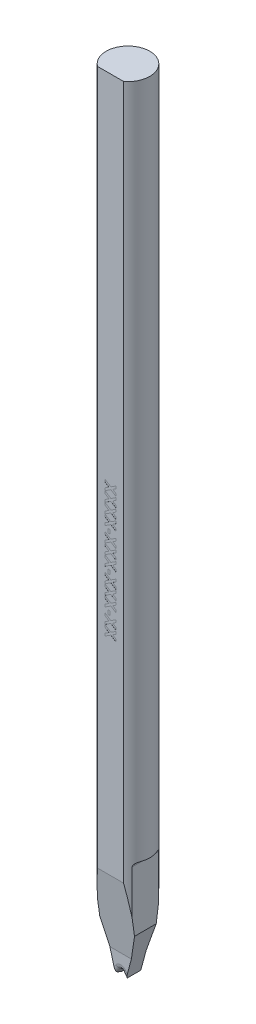
SolidWorks part; units mm, degrees
ref_plane "Ebene vorne" through (0, 0, 0) normal (0, 0, 1) x (1, 0, 0)
ref_plane "Ebene oben" through (0, 0, 0) normal (0, 1, 0) x (1, 0, 0)
ref_plane "Ebene rechts" through (0, 0, 0) normal (1, 0, 0) x (0, 0, -1)
sketch "sketch_TL_cutting" plane through (0, 0, 0) normal (0, 1, 0) x (1, 0, 0)
  circle A0 centre (0, 0) radius 1.9977
extrude "TL_cutting" add sketch "sketch_TL_cutting" along normal blind 72.009
sketch "sketch_TDF_grinding" plane through (0, 0, 0) normal (0, 1, 0) x (1, 0, 0)
  line L0 (0, 0) -> (0, -1.6015) construction
  line L1 (-2.0077, -5.6169) -> (2.0077, -5.6169)
  line L2 (-2.0077, -5.6169) -> (-2.0077, -1.6015)
  line L3 (-2.0077, -1.6015) -> (2.0077, -1.6015)
  line L4 (2.0077, -5.6169) -> (2.0077, -1.6015)
  circle A1 centre (0, 0) radius 1.9977 construction
  point P9 (0, -5.6169)
  dimension "TD_2Offset_X" = 4.0154
  dimension "TD_2Offset_Z" = 4.0154
extrude "TDF_grinding" cut sketch "sketch_TDF_grinding" along normal through all
sketch "sketch_engraving" plane through (0, 0, 1.6015) normal (0, 0, 1) x (1, 0, 0)
  line L0 (1.1942, 72.009) -> (-1.1942, 72.009) construction
  line L6 (-1.1942, 0) -> (1.1942, 0) construction
  line L7 (0, 0) -> (0, 39.605) construction
  line L8 (-0.5, 39.605) -> (-0.5, 0) construction
  text T0 "XXXX-XXX-XXX-XX" font "Arial" height 1
  dimension "D2" = 0.5
  dimension "EngravingStart" = 32.404
extrude "engraving" cut sketch "sketch_engraving" against normal blind 0.005
sketch "sketch_VW_VR_grinding" plane through (0, 0, 0) normal (0, 0, 1) x (1, 0, 0)
  line L0 (-1.59, -0.01) -> (-1.59, 9.682)
  line L1 (1.59, -0.01) -> (1.59, 9.682)
  line L2 (-1.59, 0) -> (1.59, 0) construction
  line L3 (-2.0077, 10) -> (-1.908, 10)
  line L4 (1.908, 10) -> (2.0077, 10)
  line L5 (-2.0077, 10) -> (-2.0077, -0.01)
  line L6 (-2.0077, -0.01) -> (-1.59, -0.01)
  line L7 (1.59, -0.01) -> (2.0077, -0.01)
  line L8 (2.0077, -0.01) -> (2.0077, 10)
  line L9 (-1.908, 10) -> (-1.908, 9.682) construction
  line L10 (-1.59, 9.682) -> (-1.908, 9.682) construction
  line L11 (1.59, 9.682) -> (1.908, 9.682) construction
  line L12 (1.908, 10) -> (1.908, 9.682) construction
  arc A0 (-1.908, 10) -> (-1.59, 9.682) centre (-1.908, 9.682) cw
  arc A2 (1.59, 9.682) -> (1.908, 10) centre (1.908, 9.682) cw
  dimension "D1" = 0.01
  dimension "D4" = 4.0154
extrude "VW_VR_grinding" cut sketch "sketch_VW_VR_grinding" against normal blind 2.0077 and the other way blind 2.0077
sketch "sketch_ISA_grinding" plane through (0, 0, 0) normal (0, 0, 1) x (1, 0, 0)
  line L0 (-0.5004, 0) -> (-2.0077, 5.6254)
  line L4 (2.0077, 5.6254) -> (0.5004, 0)
  line L5 (0.5004, 0) -> (-0.5004, 0)
  line L6 (0, 0) -> (0, 30.49) construction
  line L7 (-2.0077, 5.6254) -> (-2.0077, -0.01)
  line L12 (-2.0077, -0.01) -> (2.0077, -0.01)
  line L13 (2.0077, -0.01) -> (2.0077, 5.6254)
  dimension "ISA" = 30
  dimension "TD_2Offset" = 4.0154
  dimension "Offset" = 0.01
extrude "ISA_grinding" cut sketch "sketch_ISA_grinding" against normal blind 2.0077 and the other way blind 2.0077
sketch "sketch_pre_FRX_BRX" plane through (0, 0, 0) normal (1, 0, 0) x (0, 0, -1)
  line L0 (1.9977, -0.01) -> (1.9977, 3.9152) construction
  line L1 (-1.6015, -0.01) -> (-1.6015, 1.7909) construction
  line L2 (-0.6744, -0.01) -> (-0.6744, 1.7909)
  line L3 (-0.6744, 1.7909) -> (-2.0077, 1.7909)
  line L4 (-2.0077, 1.7909) -> (-2.0077, -0.01)
  line L5 (-2.0077, -0.01) -> (-0.6744, -0.01)
  line L6 (0.6744, -0.01) -> (0.6744, 1.7909)
  line L7 (0.6744, 1.7909) -> (2.0077, 1.7909)
  line L8 (2.0077, 1.7909) -> (2.0077, -0.01)
  line L9 (2.0077, -0.01) -> (0.6744, -0.01)
  dimension "D3" = 0.01
  dimension "D4" = 1.8009
  dimension "D5" = 4.0154
  dimension "D6" = 1.3487
  dimension "D2" = 0.01
  dimension "D7" = 2.6721
extrude "pre_FRX_BRX" cut sketch "sketch_pre_FRX_BRX" against normal blind 2.0077 and the other way blind 2.0077
sketch "sketch_contour_V-Groove" plane through (0, 0, 0) normal (1, 0, 0) x (0, 0, -1)
  line L0 (-1.6015, 0.3556) -> (0, 0.3556)
  line L1 (0, 0.3556) -> (1.9977, 0.3556)
  line L2 (1.9977, -0.8411) -> (1.9977, 1.3178) construction
  line L3 (-1.6015, -0.9209) -> (-1.6015, 1.9363) construction
  line L4 (-1.6015, 0) -> (1.9977, 0) construction
  line L5 (0.6744, 0) -> (0.6744, 0.3556) construction
  line L6 (-0.6744, 0) -> (-0.6744, 0.3556) construction
  dimension "D1" = 0
ref_plane "front" through (0, 0, 1.6015) normal (0, 0, 1) x (1, 0, 0)
ref_plane "back" through (0, 0, -1.9977) normal (0, 0, 1) x (1, 0, 0)
sketch "sketch_section_V-Groove" plane through (0, 0, 1.6015) normal (0, 0, 1) x (1, 0, 0)
  line L0 (-2.7655, -3.556) -> (-0.0419, 0.3338)
  line L2 (0.0419, 0.3338) -> (2.7655, -3.556)
  line L3 (-2.7655, -3.556) -> (2.7655, -3.556)
  line L4 (0, -3.556) -> (0, 0.3556) construction
  line L5 (-0.2756, 0) -> (0.2756, 0) construction
  arc A0 (0.0419, 0.3338) -> (-0.0419, 0.3338) centre (0, 0.3045) ccw
  dimension "GA" = 70
sweep "V-Groove_EDM" cut profiles "sketch_section_V-Groove" path "sketch_contour_V-Groove"
fillet "FR_EDM" radius 0.5004 3 edges at (0.1587, 0.1669, 0.6744) (0, 0.3556, 0.6744) (-0.1587, 0.1669, 0.6744)
fillet "BR_EDM" radius 0.2489 3 edges at (0.1587, 0.1669, -0.6744) (0, 0.3556, -0.6744) (-0.1587, 0.1669, -0.6744)
sketch "sketch_FA_BA_grinding" plane through (0, 0, 0) normal (1, 0, 0) x (0, 0, -1)
  line L2 (2.9977, 18.3323) -> (2.9977, -0.1)
  line L3 (2.9977, -0.1) -> (0.6744, -0.1)
  line L5 (0.6744, -0.1) -> (0.6744, 1.8009)
  line L6 (0.6744, 1.8009) -> (2.9977, 18.3323)
  line L7 (1.9977, -0.1) -> (1.9977, 11.2169) construction
  line L8 (-1.6015, 8.3975) -> (-1.6015, -0.1) construction
  line L9 (-3.6221, 22.7749) -> (-0.6744, 1.8009)
  line L10 (-0.6744, 1.8009) -> (-0.6744, -0.1)
  line L11 (-0.6744, -0.1) -> (-3.6221, -0.1)
  line L12 (-3.6221, -0.1) -> (-3.6221, 22.7749)
  line L13 (-0.6744, 1.8009) -> (0.6744, 1.8009) construction
  dimension "D4" = 1
  dimension "D1" = 0.1
  dimension "FA" = 8
  dimension "BA" = 8
extrude "FA_BA_grinding" cut sketch "sketch_FA_BA_grinding" against normal blind 2.0077 and the other way blind 2.0077
sketch "sketch_groove_dimensions" plane through (0, 0, 0) normal (1, 0, 0) x (0, 0, -1)
  line L0 (-0.174, 0.3556) -> (0.4255, 0.3556)
  line L1 (-0.6744, 0) -> (-0.6744, 0.856) construction
  line L2 (1.9977, 0) -> (1.9977, 0.4166) construction
  line L3 (0.6744, 0) -> (0.6744, 0.6045) construction
  line L4 (-1.6015, 0) -> (-1.6015, 0.3999) construction
  arc A0 (0.4255, 0.3556) -> (0.6744, 0.6045) centre (0.4255, 0.6045) ccw
  arc A1 (-0.174, 0.3556) -> (-0.6744, 0.856) centre (-0.174, 0.856) cw
equation "\"_Offset\"=0.01mm"
equation "\"TL\"=72.009mm"
equation "\"TD\"=3.99542mm"
equation "\"TDF\"=3.59918mm"
equation "\"BA\"=8deg"
equation "\"ISA\"=30deg"
equation "\"FA\"=8deg"
equation "\"GR\"=0.0508mm"
equation "\"GA\"=70deg"
equation "\"GD\"=0.3556mm"
equation "\"FL\"=1.34874mm"
equation "\"F\"=0.59944mm"
equation "\"FX\"=0mm"
equation "\"B\"=0.55118mm"
equation "\"VW\"=3.18008mm"
equation "\"cleaned_VR\"= IIF ( \"VR\" > 0 , \"VR\" , \"E\" - \"_Offset\" )"
equation "\"cleaned_VW\"= IIF ( \"VW\" > 0 , \"VW\" , \"TD\" - \"_Offset\" )"
equation "\"back_edge\"= \"TD\" / 2 - \"X\""
equation "\"side_edge_Offset\"= \"TD\" / 2 + \"_Offset\""
equation "\"TD@sketch_TL_cutting\"=\"TD\""
equation "\"TL@TL_cutting\"=\"TL\""
equation "\"TDF@sketch_TDF_grinding\"=\"TDF\""
equation "\"TD_2Offset_X@sketch_TDF_grinding\"=\"TD\"+2*\"_Offset\""
equation "\"TD_2Offset_Z@sketch_TDF_grinding\"=\"TD\"+2*\"_Offset\""
equation "\"TL_Offset\"= \"TL\" + \"_Offset\""
equation "\"ISA@sketch_ISA_grinding\"=\"ISA\""
equation "\"W@sketch_ISA_grinding\"=\"W\""
equation "\"TD_2Offset@sketch_ISA_grinding\"=\"TD\"+2*\"_Offset\""
equation "\"Offset@sketch_ISA_grinding\"=\"_Offset\""
equation "\"05TD_Offset_posZ@ISA_grinding\"=\"side_edge_Offset\""
equation "\"05TD_Offset_negZ@ISA_grinding\"=\"side_edge_Offset\""
equation "\"E\"=1.80086mm"
equation "\"cleaned_X\"= IIF ( \"X\" > 0 , \"X\" , \"TD\" / 2 - \"FL\" / 2 )"
equation "\"FR\"=0.50038mm"
equation "\"BR\"=0.24892mm"
equation "\"D1\"= \"side_edge_Offset\""
equation "\"D2\"= \"side_edge_Offset\""
equation "\"TDF@sketch_FA_BA_grinding\" = \"TDF\""
equation "\"FL@sketch_FA_BA_grinding\"=\"FL\""
equation "\"E@sketch_FA_BA_grinding\" = \"E\""
equation "\"D1@FA_BA_grinding\"=\"side_edge_Offset\""
equation "\"D2@FA_BA_grinding\"=\"side_angle_Offset\""
equation "\"10GD@sketch_section_V-Groove\" = 10 * \"GD\""
equation "\"GA@sketch_section_V-Groove\" = \"GA\""
equation "\"GD@sketch_section_V-Groove\" = \"GD\""
equation "\"B@sketch_section_V-Groove\" = \"B\""
equation "\"GD@sketch_contour_V-Groove\" = \"GD\""
equation "\"cleaned_FRX\"= IIF ( \"FRX\" > 0 , \"FRX\" , \"FR\" )"
equation "\"cleaned_BRX\"= IIF ( \"BRX\" > 0 , \"BRX\" , \"BR\" )"
equation "\"FL_groove_angle\"=0deg"
equation "\"D3@sketch_pre_FRX_BRX\" = \"_Offset\""
equation "\"D4@sketch_pre_FRX_BRX\" = \"E\""
equation "\"D5@sketch_pre_FRX_BRX\" = 2 * \"side_edge_Offset\""
equation "\"D6@sketch_pre_FRX_BRX\" = \"FL\" + ( \"FR\" - \"cleaned_FRX\" ) + ( \"BR\" - \"cleaned_BRX\" )"
equation "\"TD/2@sketch_pre_FRX_BRX\" = \"TD\" / 2"
equation "\"TDF@sketch_pre_FRX_BRX\" = \"TDF\""
equation "\"D2@sketch_pre_FRX_BRX\" = \"_Offset\""
equation "\"D1@pre_FRX_BRX\" = \"side_edge_Offset\""
equation "\"D2@pre_FRX_BRX\" = \"side_edge_Offset\""
equation "\"D1@BR_EDM\"=\"BR\""
equation "\"TD/2@sketch_FA_BA_grinding\" = \"TD\" / 2"
equation "\"TD/2@sketch_contour_V-Groove\" = \"TD\" / 2"
equation "\"TDF@sketch_contour_V-Groove\" = \"TDF\""
equation "\"D1@sketch_contour_V-Groove\"=\"FL_groove_angle\""
equation "\"FL@sketch_contour_V-Groove\"=\"FL\""
equation "\"FL/2@sketch_contour_V-Groove\" = \"FL\" / 2"
equation "\"D1@FR_EDM\"=\"FR\""
equation "\"D1@sketch_VW_VR_grinding\" = \"_Offset\""
equation "\"D4@sketch_VW_VR_grinding\" = 2 * \"side_edge_Offset\""
equation "\"VR@sketch_VW_VR_grinding\" = \"cleaned_VR\""
equation "\"VW@sketch_VW_VR_grinding\"=\"cleaned_VW\""
equation "\"D1@VW_VR_grinding\" = \"side_edge_Offset\""
equation "\"D2@VW_VR_grinding\" = \"side_edge_Offset\""
equation "\"X\"=0.94996mm"
equation "\"VR\"=9.99998mm"
equation "\"W\"=1.00076mm"
equation "\"VW_radius\"= \"cleaned_VW\" / 10"
equation "\"VW_radius_cleaned\"= IIF ( \"VW\" > 0 , \"VW_radius\" , \"_Offset\" / 2 )"
equation "\"D2@sketch_VW_VR_grinding\"=\"VW_radius_cleaned\""
equation "\"FRX\"=0mm"
equation "\"BRX\"=0mm"
equation "\"FA@sketch_FA_BA_grinding\" = \"FA\""
equation "\"D4@sketch_FA_BA_grinding\"=\"_Offset\"*100"
equation "\"BA@sketch_FA_BA_grinding\" = \"BA\""
equation "\"D1@sketch_groove_dimensions\" = \"TD\" / 2"
equation "\"FL@sketch_groove_dimensions\" = \"FL\""
equation "\"FR@sketch_groove_dimensions\" = \"FR\""
equation "\"BR@sketch_groove_dimensions\" = \"BR\""
equation "\"FRX@sketch_groove_dimensions\" = \"cleaned_FRX\""
equation "\"BRX@sketch_groove_dimensions\" = \"cleaned_BRX\""
equation "\"GD@sketch_groove_dimensions\" = \"GD\""
equation "\"cleaned_FX\"= IIF ( \"FX\" > 0 , \"FX\" , \"TDF\" - ( \"TD\" + \"FL\" ) / 2 )"
equation "\"D7@sketch_pre_FRX_BRX\"=\"TDF\"-\"cleaned_FX\"-(\"FR\"-\"cleaned_FRX\")"
equation "\"FX@sketch_contour_V-Groove\" = \"cleaned_FX\""
equation "\"FX@sketch_FA_BA_grinding\" = \"cleaned_FX\""
equation "\"TDF@sketch_groove_dimensions\" = \"TDF\""
equation "\"FX@sketch_groove_dimensions\" = \"cleaned_FX\""
equation "\"EngravingStart\" = \"TL\" * 0.45"
equation "\"EngravingStart@sketch_engraving\" = \"EngravingStart\""
